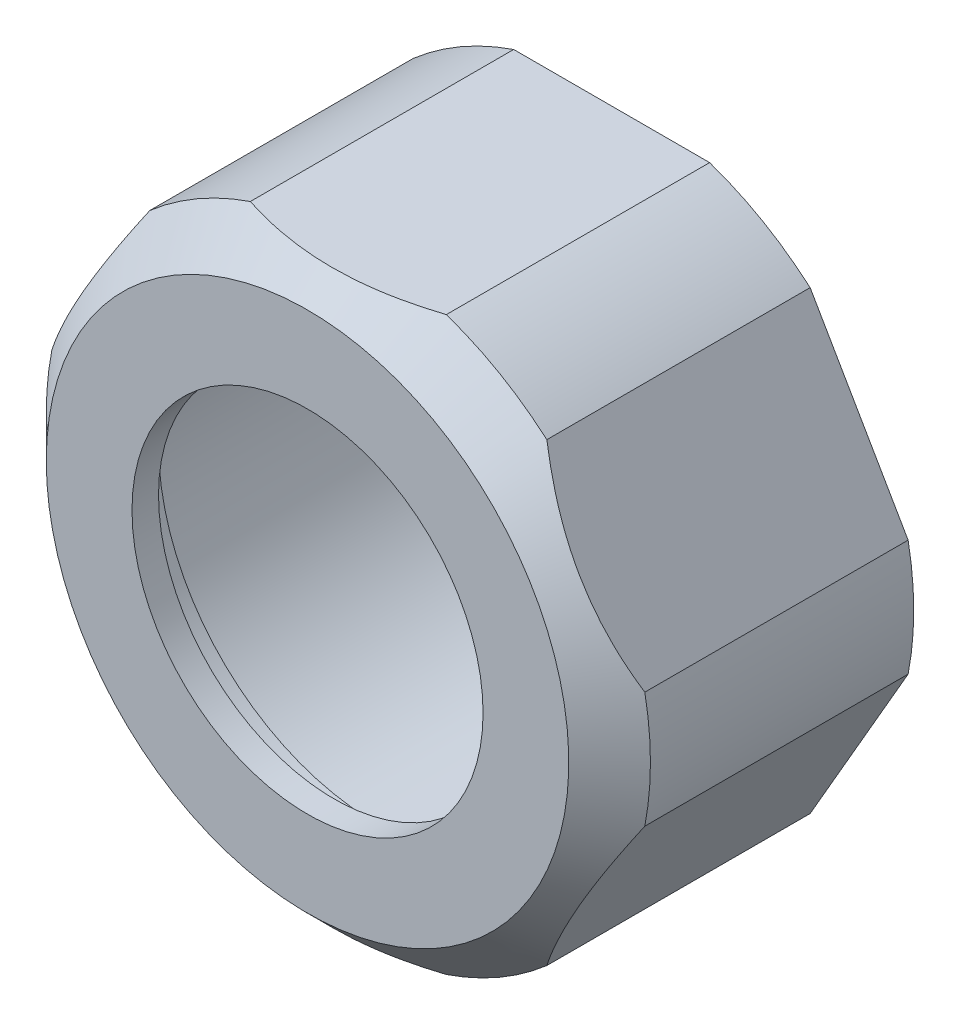
SolidWorks part; units mm, degrees
material "1060 Сплав"
ref_plane "Спереди" through (0, 0, 0) normal (0, 0, 1) x (1, 0, 0)
ref_plane "Сверху" through (0, 0, 0) normal (0, 1, 0) x (1, 0, 0)
ref_plane "Справа" through (0, 0, 0) normal (1, 0, 0) x (0, 0, -1)
sketch "Эскиз1" plane through (0, 0, 0) normal (0, 1, 0) x (1, 0, 0)
  line L0 (6.4, -7.45) -> (7.4, -6.45)
  line L1 (0, 0) -> (7.4, 0)
  line L2 (0, 0) -> (0, -7.45)
  line L3 (0, -7.45) -> (6.4, -7.45)
  line L4 (7.4, 0) -> (7.4, -6.45)
  line L5 (5.65, 0) -> (5.65, -5.75)
  line L6 (5.65, -5.75) -> (5.35, -5.75)
  line L7 (5.35, -5.75) -> (5.35, -6.8)
  line L8 (5.35, -6.8) -> (4.3, -6.8)
  line L9 (4.3, -6.8) -> (4.3, -7.45)
  point P1 (7.4, -7.45)
  dimension "D1" = 7.4
  dimension "D2" = 7.45
  dimension "D3" = 4.3
  dimension "D6" = 5.35
  dimension "D7" = 5.75
  dimension "D8" = 5.65
  dimension "D9" = 6.8
revolve "Повернуть1" add sketch "Эскиз1" angle 360 about L2
cosmetic thread "Условное изображение резьбы1" parameters "D1"=4, "D2"=14
sketch "Эскиз2" plane through (0, 0, 0) normal (0, 0, 1) x (1, 0, 0)
  line L1 (8.0829, 0) -> (4.0415, 7)
  line L2 (4.0415, 7) -> (-4.0415, 7)
  line L3 (-4.0415, 7) -> (-8.0829, 0)
  line L4 (-8.0829, 0) -> (-4.0415, -7)
  line L5 (-4.0415, -7) -> (4.0415, -7)
  line L6 (4.0415, -7) -> (8.0829, 0)
  circle A0 centre (0, 0) radius 7 construction
  circle A1 centre (0, 0) radius 10
  dimension "D1" = 14
  dimension "D2" = 20
extrude "Вырез-Вытянуть2" cut sketch "Эскиз2" along normal through all
chamfer "Фаска1" distance 0.3 angle 45 1 edges at (-5.65, 0, 0)
